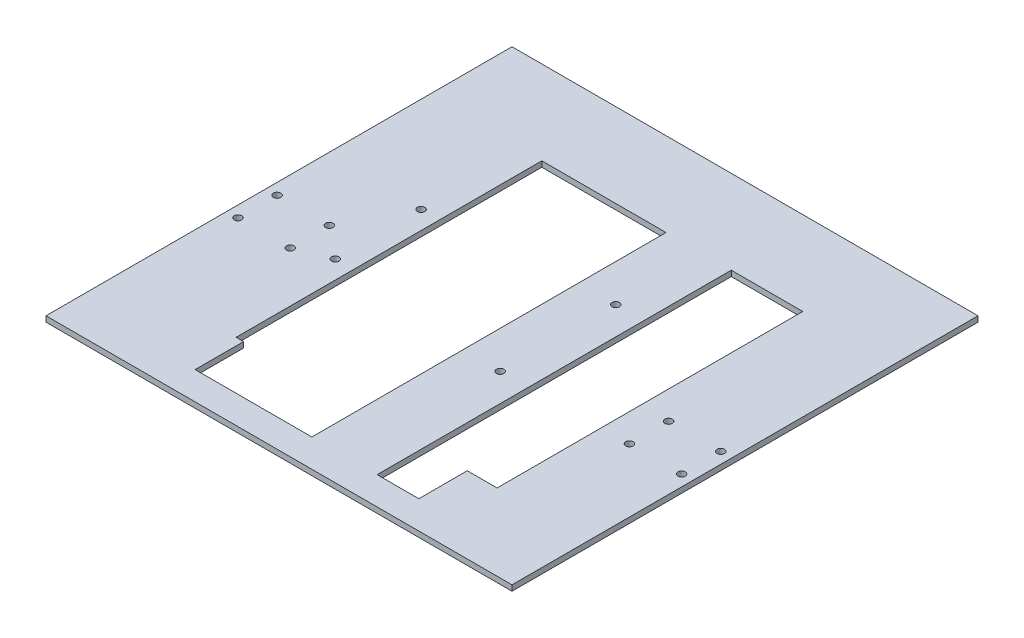
SolidWorks part; units mm, degrees
material "1060 Alloy"
ref_plane "Front Plane" through (0, 0, 0) normal (0, 0, 1) x (1, 0, 0)
ref_plane "Top Plane" through (0, 0, 0) normal (0, 1, 0) x (1, 0, 0)
ref_plane "Right Plane" through (0, 0, 0) normal (1, 0, 0) x (0, 0, -1)
sketch "Sketch1" plane through (0, 0, 0) normal (0, 1, 0) x (1, 0, 0)
  line L1 (125, 125) -> (-125, 125)
  line L2 (125, 125) -> (125, -125)
  line L3 (125, -125) -> (-125, -125)
  line L4 (-125, 125) -> (-125, -125)
  line L5 (125, 125) -> (-125, -125) construction
  line L6 (125, -125) -> (-125, 125) construction
  point P0 (0, 0)
  dimension "D1" = 250
  dimension "D2" = 250
extrude "Boss-Extrude1" add sketch "Sketch1" along normal blind 3
sketch "Sketch4" plane through (0, 3, 0) normal (0, 1, 0) x (1, 0, 0)
  circle A0 centre (91, -28) radius 2
  circle A1 centre (91, -7) radius 2
  circle A2 centre (119, -7) radius 2
  circle A3 centre (119, -28) radius 2
  circle A4 centre (22.6286, -29) radius 2
  circle A5 centre (22.6286, 33) radius 2
  circle A6 centre (-73.7764, 25) radius 2
  circle A7 centre (-73.7764, -21) radius 2
  circle A8 centre (-91, -28) radius 2
  circle A9 centre (-91, -7) radius 2
  circle A10 centre (-119, -7) radius 2
  circle A11 centre (-119, -28) radius 2
  dimension "D1" = 4
  dimension "D2" = 4
  dimension "D3" = 4
  dimension "D4" = 4
  dimension "D5" = 4
  dimension "D6" = 4
  dimension "D7" = 4
  dimension "D8" = 4
extrude "Cut-Extrude1" cut sketch "Sketch4" against normal blind 3
sketch "Sketch5" plane through (0, 3, 0) normal (0, 1, 0) x (1, 0, 0)
  line L0 (125, 125) -> (-125, 125) construction
  line L1 (2.6286, -110) -> (-60, -110)
  line L2 (2.6286, -110) -> (2.6286, 80)
  line L3 (2.6286, 80) -> (-64, 80)
  line L4 (-125, 125) -> (-125, -125) construction
  line L6 (37.6286, 80) -> (37.6286, -110)
  line L7 (37.6286, -110) -> (60, -110)
  line L8 (60, -110) -> (60, -84)
  line L9 (76, 80) -> (37.6286, 80)
  line L10 (-125, -125) -> (125, -125) construction
  line L11 (125, -125) -> (125, 125) construction
  line L12 (60, -84) -> (76, -84)
  line L13 (76, -84) -> (76, 80)
  line L15 (-60, -110) -> (-60, -84)
  line L16 (-60, -84) -> (-64, -84)
  line L17 (-64, -84) -> (-64, 80)
  circle A1 centre (22.6286, 33) radius 2 construction
  dimension "D1" = 15
  dimension "D2" = 20
  dimension "D3" = 45
  dimension "D4" = 26
  dimension "D5" = 15
  dimension "D6" = 65
  dimension "D7" = 65
  dimension "D8" = 45
  dimension "D9" = 26
extrude "Cut-Extrude2" cut sketch "Sketch5" against normal blind 3
sketch "Sketch8" plane through (0, 3, 0) normal (0, 1, 0) x (1, 0, 0)
  circle A0 centre (-112, -97) radius 2
  circle A1 centre (-112, -112) radius 2
  circle A2 centre (-73, -112) radius 2
  circle A3 centre (-73, -97) radius 2
  circle A4 centre (73, -112) radius 2
  circle A5 centre (73, -97) radius 2
  circle A6 centre (112, -97) radius 2
  circle A7 centre (112, -112) radius 2
  circle A8 centre (79.5, 95) radius 2
  circle A9 centre (79.5, 110) radius 2
  circle A10 centre (40.5, 110) radius 2
  circle A11 centre (40.5, 95) radius 2
  circle A12 centre (-40.5, 95) radius 2
  circle A13 centre (-40.5, 110) radius 2
  circle A14 centre (-79.5, 110) radius 2
  circle A15 centre (-79.5, 95) radius 2
extrude "Cut-Extrude3" [suppressed] cut sketch "Sketch8" against normal blind 3
